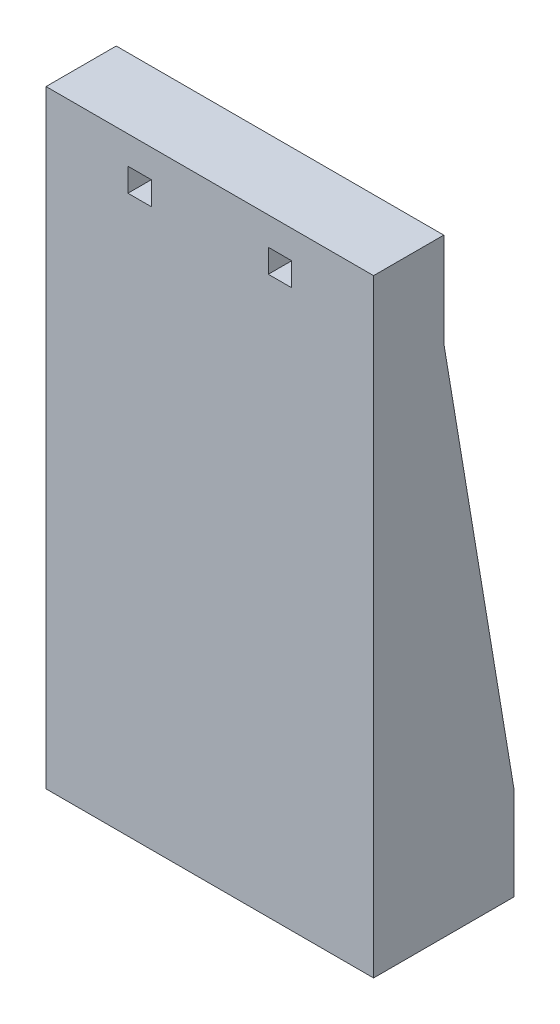
SolidWorks part; units mm, degrees
ref_plane "Front Plane" through (0, 0, 0) normal (0, 0, 1) x (1, 0, 0)
ref_plane "Top Plane" through (0, 0, 0) normal (0, 1, 0) x (1, 0, 0)
ref_plane "Right Plane" through (0, 0, 0) normal (1, 0, 0) x (0, 0, -1)
sketch "Sketch1" plane through (0, 0, 0) normal (1, 0, 0) x (0, 0, -1)
  line L1 (-15, 10) -> (15, 10)
  line L2 (-15, 10) -> (-15, -10)
  line L3 (-15, -10) -> (15, -10)
  line L4 (15, 10) -> (15, -10)
  line L5 (-15, 10) -> (15, -10) construction
  line L6 (-15, -10) -> (15, 10) construction
  line L7 (-15, 10) -> (-10, 10)
  line L8 (-15, 10) -> (-15, 120)
  line L9 (-15, 120) -> (-10, 120)
  line L10 (-10, 10) -> (-10, 120)
  point P0 (0, 0)
  dimension "D1" = 30
  dimension "D2" = 20
  dimension "D3" = 110
  dimension "D4" = 5
extrude "Boss-Extrude1" add sketch "Sketch1" along normal mid plane 70 contours L1 L10 L9 L8 | L4 L1 L2 L3
sketch "Sketch2" plane through (0, 0, -15) normal (0, 0, -1) x (-1, 0, 0)
  circle A0 centre (0, 0) radius 20
  dimension "D1" = 40
extrude "Cut-Extrude1" [suppressed] cut sketch "Sketch2" against normal through all
thread "Thread1" [suppressed] pitch 6 start angle 0, offset 7, length 100, pitch 6, diameter 40
ref_plane "Plane1" through (20, 0, -22) normal (0, -1, 0) x (1, 0, 0)
sketch "Thread Profile1" plane through (20, 0, -22) normal (0, -1, 0) x (1, 0, 0)
  line L0 (0, 0) -> (0, 6) construction
  line L1 (0, 0) -> (3.2476, 1.875)
  line L2 (3.2476, 1.875) -> (3.2476, 2.625)
  line L3 (3.2476, 2.625) -> (0, 4.5)
  line L4 (3.2476, 2.25) -> (0, 2.25) construction
  line L11 (0, 0) -> (0, 4.5)
  point P2 (0, 0)
  dimension "Pitch" = 6
  dimension "Profile_Angle" = 60
  dimension "Profile_Land" = 0.75
  dimension "Profile_Height" = 3.2476
chamfer "Chamfer1" [suppressed] distance 4 angle 45
chamfer "Chamfer2" [suppressed] distance 4 angle 45
sketch "Sketch9" plane through (35, 0, 0) normal (1, 0, 0) x (0, 0, -1)
  line L1 (-10, 120) -> (0, 120)
  line L2 (-10, 120) -> (-10, 100)
  line L3 (-10, 100) -> (0, 100)
  line L4 (0, 120) -> (0, 100)
  dimension "D1" = 10
  dimension "D2" = 20
extrude "Boss-Extrude2" add sketch "Sketch9" against normal through all
sketch "Sketch10" plane through (35, 0, 0) normal (1, 0, 0) x (0, 0, -1)
  line L0 (0, 100) -> (15, 10)
rib "Rib1" sketch "Sketch10" sketch "Sketch10" thickness 4 extrusion direction parallel to sketch draft on no parameters "D1"=4
mirror "Mirror1" about plane through (0, 0, 0) normal (1, 0, 0) of "Rib1"
sketch "Sketch11" plane through (0, 0, 15) normal (0, 0, 1) x (1, 0, 0)
  line L0 (-15, 111.5) -> (15, 111.5) construction
  line L1 (17.5, 114) -> (12.5, 114)
  line L2 (17.5, 114) -> (17.5, 109)
  line L3 (17.5, 109) -> (12.5, 109)
  line L4 (12.5, 114) -> (12.5, 109)
  line L5 (17.5, 114) -> (12.5, 109) construction
  line L6 (17.5, 109) -> (12.5, 114) construction
  line L7 (-12.5, 114) -> (-17.5, 114)
  line L8 (-12.5, 114) -> (-12.5, 109)
  line L9 (-12.5, 109) -> (-17.5, 109)
  line L10 (-17.5, 114) -> (-17.5, 109)
  line L11 (-12.5, 114) -> (-17.5, 109) construction
  line L12 (-12.5, 109) -> (-17.5, 114) construction
  line L14 (35, 120) -> (-35, 120) construction
  point P0 (15, 111.5)
  point P5 (-15, 111.5)
  point P10 (0, 111.5)
  dimension "D1" = 5
  dimension "D2" = 30
  dimension "D3" = 6
extrude "Cut-Extrude2" cut sketch "Sketch11" against normal blind 10 contours L2 L3 L4 L1 | L7 L10 L9 L8
